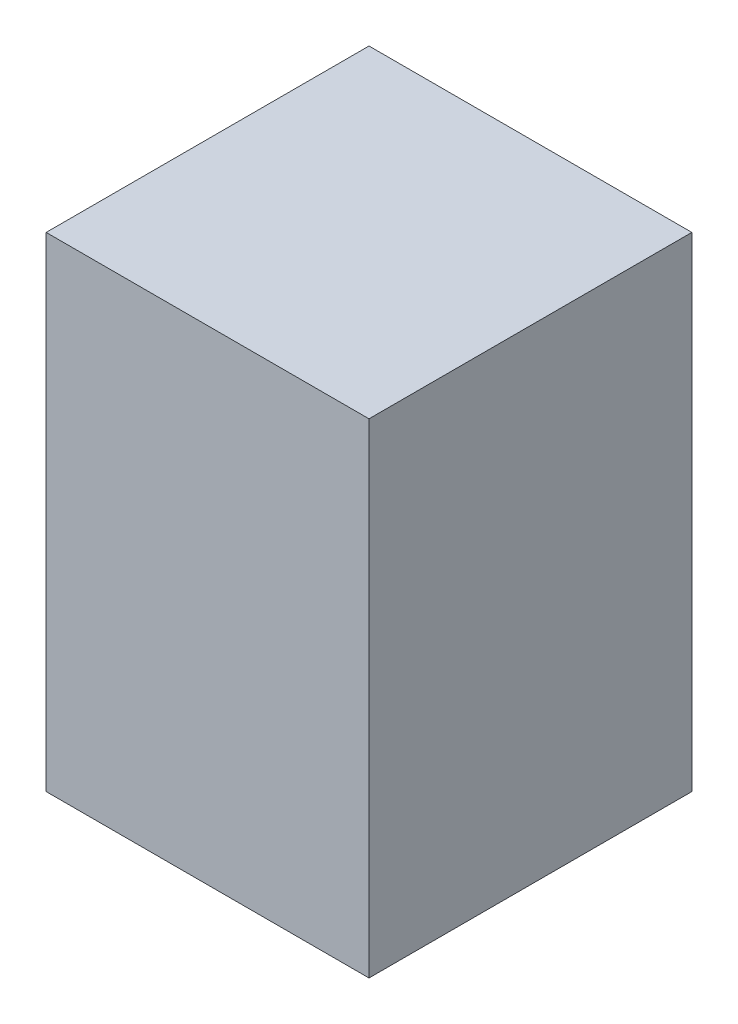
SolidWorks part; units mm, degrees
ref_plane "Front Plane" through (0, 0, 0) normal (0, 0, 1) x (1, 0, 0)
ref_plane "Top Plane" through (0, 0, 0) normal (0, 1, 0) x (1, 0, 0)
ref_plane "Right Plane" through (0, 0, 0) normal (1, 0, 0) x (0, 0, -1)
other "Configuration Table"
sketch "Sketch1" plane through (0, 0, 0) normal (0, 0, 1) x (1, 0, 0)
  line L1 (60, 0) -> (140, 0)
  line L2 (60, 0) -> (60, 120)
  line L3 (60, 120) -> (140, 120)
  line L4 (140, 0) -> (140, 120)
extrude "PRESS_ayak_3_1" add sketch "Sketch1" against normal blind 80 from offset 680 separate body
